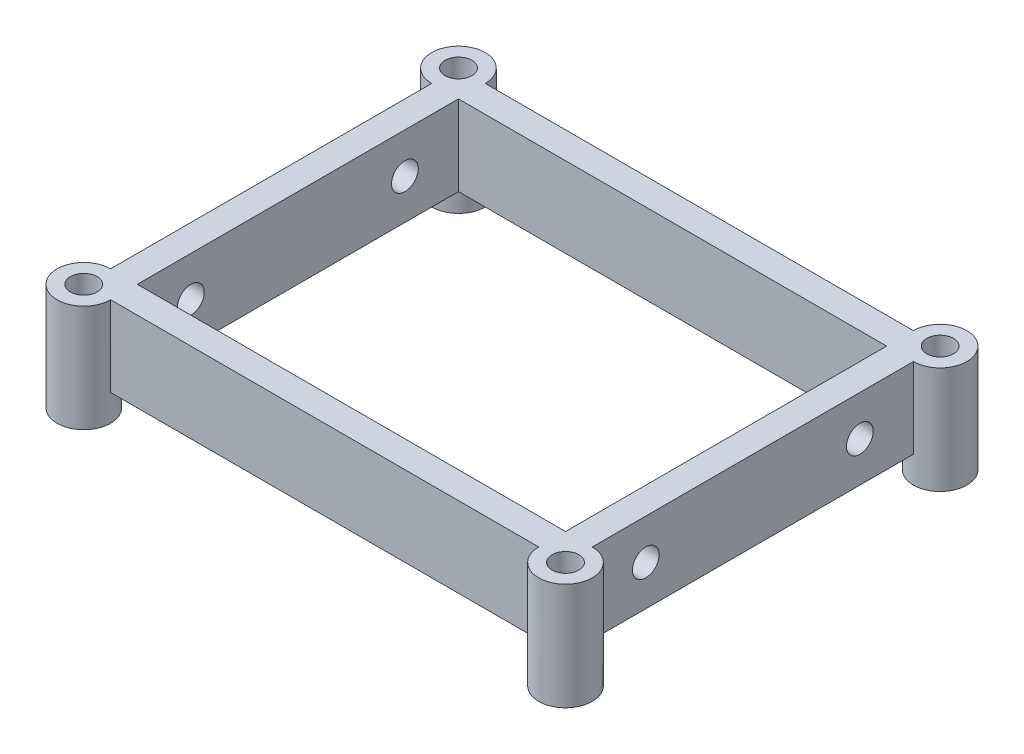
SolidWorks part; units mm, degrees
ref_plane "前视基准面" through (0, 0, 0) normal (0, 0, 1) x (1, 0, 0)
ref_plane "上视基准面" through (0, 0, 0) normal (0, 1, 0) x (1, 0, 0)
ref_plane "右视基准面" through (0, 0, 0) normal (1, 0, 0) x (0, 0, -1)
sketch "草图1" plane through (0, 0, 0) normal (0, 1, 0) x (1, 0, 0)
  line L1 (0, 30) -> (80, 30)
  line L2 (0, 30) -> (0, -30)
  line L3 (0, -30) -> (80, -30)
  line L4 (80, 30) -> (80, -30)
  line L5 (-5, 35) -> (85, 35)
  line L6 (-5, 35) -> (-5, -35)
  line L7 (-5, -35) -> (85, -35)
  line L8 (85, 35) -> (85, -35)
  dimension "D1" = 60
  dimension "D2" = 80
  dimension "D3" = 70
  dimension "D4" = 90
  dimension "D5" = 5
  dimension "D6" = 5
extrude "凸台-拉伸1" add sketch "草图1" along normal blind 15
sketch "草图2" plane through (85, 0, 0) normal (1, 0, 0) x (0, 0, -1)
  line L0 (0, -0.5307) -> (0, 17.2536) construction
  line L2 (-35, 0) -> (35, 0) construction
  circle A0 centre (20, 7.5) radius 2.5
  circle A1 centre (-20, 7.5) radius 2.5
  dimension "D1" = 5
  dimension "D2" = 20
  dimension "D3" = 7.5
extrude "切除-拉伸1" cut sketch "草图2" against normal through all
sketch "草图3" plane through (0, 15, 0) normal (0, 1, 0) x (1, 0, 0)
  line L0 (-8.25, 0) -> (8.25, 0) construction
  circle A0 centre (85, 35) radius 5
  circle A1 centre (85, -35) radius 5
  circle A2 centre (-5, -35) radius 5
  circle A3 centre (-5, 35) radius 5
  dimension "D1" = 10
  dimension "D2" = 10
  dimension "D3" = 10
  dimension "D4" = 10
extrude "凸台-拉伸3" add sketch "草图3" against normal blind 15
sketch "草图5" plane through (0, 15, 0) normal (0, 1, 0) x (1, 0, 0)
  circle A0 centre (-5, -35) radius 2.5
  circle A1 centre (-5, 35) radius 2.5
  circle A2 centre (85, 35) radius 2.5
  circle A3 centre (85, -35) radius 2.5
  dimension "D1" = 5
  dimension "D2" = 5
  dimension "D3" = 5
  dimension "D4" = 5
extrude "切除-拉伸2" cut sketch "草图5" against normal blind 15
sketch "草图6" plane through (0, 15, 0) normal (0, 1, 0) x (1, 0, 0)
  line L0 (40, 35) -> (40, -35) construction
  line L1 (80, 35) -> (0, 35) construction
  line L2 (0, -35) -> (80, -35) construction
sketch "草图8" plane through (0, 0, 0) normal (0, -1, 0) x (1, 0, 0)
  line L0 (40, -35) -> (40, 35) construction
  line L1 (80, -35) -> (0, -35) construction
  line L2 (0, 35) -> (80, 35) construction
ref_plane "基准面1" through (40, 0, 0) normal (1, 0, 0) x (0, 0, -1)
sketch "草图9" plane through (40, 0, 0) normal (1, 0, 0) x (0, 0, -1)
  line L0 (0, 0) -> (0, 17.456) construction
sketch "草图10" plane through (0, 15, 0) normal (0, 1, 0) x (1, 0, 0)
  line L0 (65, 35) -> (65, -35) construction
  line L1 (80, 35) -> (0, 35) construction
  line L2 (0, -35) -> (80, -35) construction
  line L3 (15, 35) -> (15, -35) construction
  line L4 (40, 35) -> (40, -35) construction
  dimension "D1" = 25
  dimension "D2" = 25
sketch "草图11" plane through (0, 0, 0) normal (0, -1, 0) x (1, 0, 0)
  line L0 (15, 35) -> (15, -35) construction
  line L1 (0, 35) -> (80, 35) construction
  line L2 (80, -35) -> (0, -35) construction
  line L3 (65, 35) -> (65, -35) construction
  line L4 (40, -35) -> (40, 35) construction
  line L5 (85, -25) -> (-5, -25) construction
  line L6 (85, 30) -> (85, -30) construction
  line L7 (-5, -30) -> (-5, 30) construction
  line L8 (80, -30) -> (0, -30) construction
  dimension "D1" = 25
  dimension "D2" = 25
  dimension "D3" = 5
sketch "草图12" plane through (0, 15, 0) normal (0, 1, 0) x (1, 0, 0)
  line L0 (85, 25) -> (-5, 25) construction
  line L1 (85, -30) -> (85, 30) construction
  line L2 (-5, 30) -> (-5, -30) construction
  line L3 (80, 30) -> (0, 30) construction
  dimension "D1" = 5
ref_plane "基准面2" through (65, 0, 0) normal (1, 0, 0) x (0, 0, -1)
ref_plane "基准面3" through (0, 0, -25) normal (0, 0, 1) x (1, 0, 0)
sketch "草图13" plane through (0, 0, 0) normal (0, -1, 0) x (1, 0, 0)
  line L0 (40, -8.25) -> (40, 8.25) construction
  circle A0 centre (85, -35) radius 5
  circle A1 centre (85, -35) radius 2.5
  circle A2 centre (85, 35) radius 5
  circle A3 centre (85, 35) radius 2.5
  circle A4 centre (-5, 35) radius 2.5
  circle A5 centre (-5, 35) radius 5
  circle A6 centre (-5, -35) radius 2.5
  circle A7 centre (-5, -35) radius 5
extrude "凸台-拉伸4" add sketch "草图13" along normal blind 5
